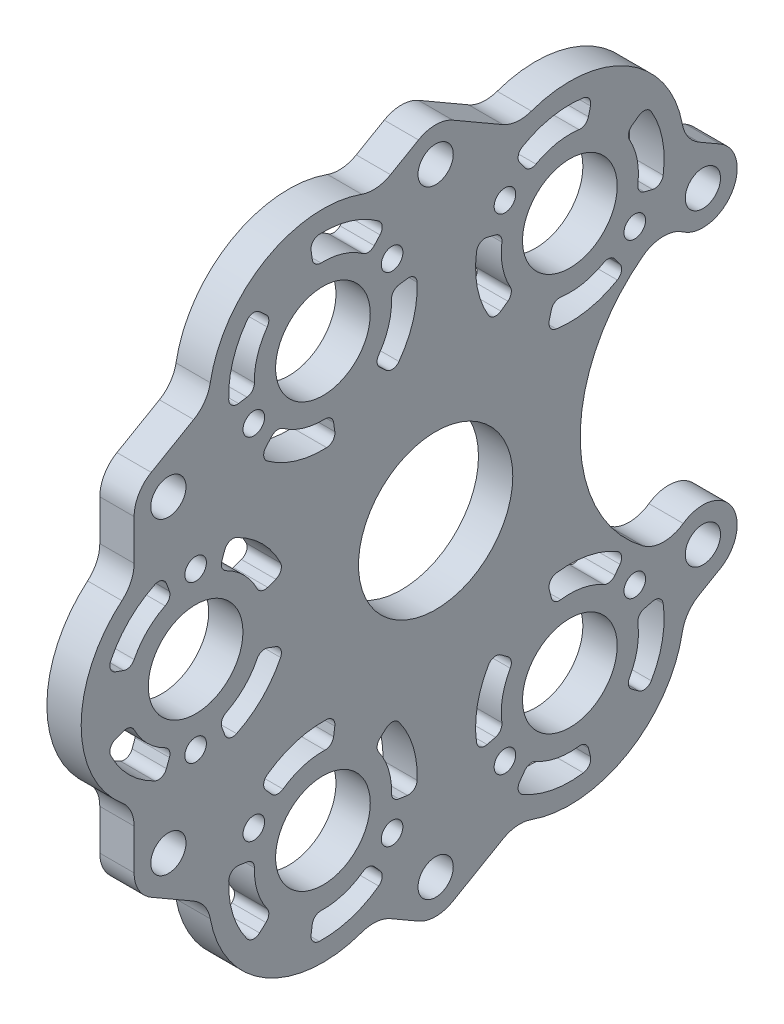
SolidWorks part; units mm, degrees
material "6061-T6 (SS)"
ref_plane "Front Plane" through (0, 0, 0) normal (0, 0, 1) x (1, 0, 0)
ref_plane "Top Plane" through (0, 0, 0) normal (0, 1, 0) x (1, 0, 0)
ref_plane "Right Plane" through (0, 0, 0) normal (1, 0, 0) x (0, 0, -1)
sketch "Sketch1" plane through (0, 0, 0) normal (1, 0, 0) x (0, 0, -1)
  line L0 (-49.4934, 28.575) -> (-49.4934, -28.575) construction
  line L1 (-49.4934, -28.575) -> (0, -57.15) construction
  line L2 (0, -57.15) -> (49.4934, -28.575) construction
  line L3 (49.4934, -28.575) -> (49.4934, 28.575) construction
  line L4 (49.4934, 28.575) -> (0, 57.15) construction
  line L5 (0, 57.15) -> (-49.4934, 28.575) construction
  line L6 (-55.8434, 32.2412) -> (-55.8434, -32.2412)
  line L7 (-55.8434, -32.2412) -> (0, -64.4823)
  line L8 (0, -64.4823) -> (55.8434, -32.2412)
  line L10 (55.8434, 32.2412) -> (0, 64.4823)
  line L11 (0, 64.4823) -> (-55.8434, 32.2412)
  line L12 (55.8434, -32.2412) -> (55.8434, 32.2412) construction
  line L13 (55.8434, -32.2412) -> (55.8434, -29.0662)
  line L14 (55.8434, -29.0662) -> (55.8434, 29.0662)
  line L15 (55.8434, 29.0662) -> (55.8434, 32.2412)
  circle A0 centre (49.4934, -28.575) radius 3.2639 construction
  circle A1 centre (0, 57.15) radius 3.2639 construction
  circle A2 centre (49.4934, 28.575) radius 3.2639 construction
  circle A3 centre (0, -57.15) radius 3.2639 construction
  circle A4 centre (-49.4934, -28.575) radius 3.2639 construction
  circle A5 centre (-49.4934, 28.575) radius 3.2639 construction
  circle A6 centre (49.4934, -28.575) radius 3.2639
  circle A7 centre (0, 57.15) radius 3.2639
  circle A8 centre (49.4934, 28.575) radius 3.2639
  circle A9 centre (0, -57.15) radius 3.2639
  circle A10 centre (-49.4934, -28.575) radius 3.2639
  circle A11 centre (-49.4934, 28.575) radius 3.2639
  circle A12 centre (-44.45, 14.4996) radius 2 construction
  circle A13 centre (-44.45, -14.4996) radius 2 construction
  circle A14 centre (-33.6704, -32.4399) radius 2 construction
  circle A15 centre (-8.0656, -46.0542) radius 2 construction
  circle A16 centre (12.8354, -44.9588) radius 2 construction
  circle A17 centre (36.8768, -28.7427) radius 2 construction
  circle A18 centre (36.8768, 28.7427) radius 2 construction
  circle A19 centre (12.8354, 44.9588) radius 2 construction
  circle A20 centre (-8.0656, 46.0542) radius 2 construction
  circle A21 centre (-33.6704, 32.4399) radius 2 construction
  circle A22 centre (-44.45, 0) radius 8.763 construction
  circle A23 centre (-20.868, -39.247) radius 8.763 construction
  circle A24 centre (24.8561, -36.8507) radius 8.763 construction
  circle A25 centre (24.8561, 36.8507) radius 8.763 construction
  circle A26 centre (-20.868, 39.247) radius 8.763 construction
  circle A27 centre (-44.45, 14.4996) radius 2
  circle A28 centre (-44.45, -14.4996) radius 2
  circle A29 centre (-33.6704, -32.4399) radius 2
  circle A30 centre (-8.0656, -46.0542) radius 2
  circle A31 centre (12.8354, -44.9588) radius 2
  circle A32 centre (36.8768, -28.7427) radius 2
  circle A33 centre (36.8768, 28.7427) radius 2
  circle A34 centre (12.8354, 44.9588) radius 2
  circle A35 centre (-8.0656, 46.0542) radius 2
  circle A36 centre (-33.6704, 32.4399) radius 2
  circle A37 centre (-44.45, 0) radius 8.763
  circle A38 centre (-20.868, -39.247) radius 8.763
  circle A39 centre (24.8561, -36.8507) radius 8.763
  circle A40 centre (24.8561, 36.8507) radius 8.763
  circle A41 centre (-20.868, 39.247) radius 8.763
  circle A42 centre (-20.868, -39.247) radius 21.1963 construction
  circle A43 centre (24.8561, -36.8507) radius 21.1963 construction
  circle A44 centre (24.8561, 36.8507) radius 21.1963 construction
  circle A45 centre (-20.868, 39.247) radius 21.1963 construction
  circle A46 centre (-44.45, 0) radius 21.1963 construction
  circle A47 centre (-20.868, -39.247) radius 21.1963
  circle A48 centre (24.8561, -36.8507) radius 21.1963
  circle A49 centre (24.8561, 36.8507) radius 21.1963
  circle A50 centre (-20.868, 39.247) radius 21.1963
  circle A51 centre (-44.45, 0) radius 21.1963
  arc A53 (55.8434, -29.0662) -> (55.8434, 29.0662) centre (55.8434, 0) cw
  circle A56 centre (49.4934, -28.575) radius 6.35
  circle A57 centre (49.4934, 28.575) radius 6.35
  circle A58 centre (0, 0) radius 14.2875 construction
  circle A59 centre (0, 0) radius 14.2875
  dimension "D3" = 12.7
  dimension "D2" = 3.175
  dimension "D1" = 6.35
extrude "Boss-Extrude1" add sketch "Sketch1" against normal blind 6.35 contours L13 A53 L15 L10 A49 L11 A50 L6 A51 L7 A47 L8 A48 A11 A10 A9 A8 A7 A6 | L6 A51 A27 A28 A37 | L11 A50 A35 A36 A41 | L10 A49 A33 A34 A40 | L10 A49 | L11 A50 | L8 A48 A31 A32 A39 | L7 A47 A29 A30 A38 | L7 A47 | L6 A51 | L8 A48 | A53 A56 A6 | A56 A53 A6 | A57 A53 A8 | A53 A57 A8 | A49 A57 | A57 L10 A49 | A56 A48 L8 | A48 A56 | A56 A53 A48 | A57 A49 A53
fillet "Fillet1" radius 6.35 16 edges at (-3.175, -55.7136, -15.1879) (-3.175, -37.9092, -46.026) (-3.175, -64.4823, 0) (-3.175, -40.2091, 42.0425) (-3.175, -58.0657, 11.114) (-3.175, -32.2412, 55.8434) (-3.175, 17.8739, 55.8434) (-3.175, -17.8739, 55.8434) (-3.175, 32.2412, 55.8434) (-3.175, 37.9092, -46.026) (-3.175, 55.7136, -15.1879) (-3.175, 64.4823, 0) (-3.175, 58.0657, 11.114) (-3.175, 40.2091, 42.0425) (-3.175, -26.3386, -43.5502) (-3.175, 26.3386, -43.5502)
sketch "Sketch2" plane through (-6.35, 0, 0) normal (-1, 0, 0) x (0, 0, 1)
  line L3 (28.0406, 5.9725) -> (44.45, 0)
  line L4 (44.45, 0) -> (38.4775, 16.4094)
  line L5 (44.45, 0) -> (26.9875, 0) construction
  line L6 (44.45, 17.4625) -> (44.45, 0) construction
  line L7 (41.4637, 8.2047) -> (36.2453, 2.9863) construction
  line L8 (36.2453, 2.9863) -> (36.2453, 0) construction
  line L9 (41.4637, 8.2047) -> (44.45, 8.2047) construction
  line L10 (50.4225, 16.4094) -> (44.45, 0)
  line L11 (44.45, 0) -> (60.8594, 5.9725)
  line L12 (60.8594, -5.9725) -> (44.45, 0)
  line L13 (44.45, 0) -> (50.4225, -16.4094)
  line L14 (38.4775, -16.4094) -> (44.45, 0)
  line L15 (44.45, 0) -> (28.0406, -5.9725)
  circle A0 centre (44.45, 0) radius 17.4625
  circle A1 centre (44.45, 0) radius 12.7
  point P21 (44.45, 0)
  dimension "D2" = 25.4
  dimension "D3" = 34.925
  dimension "D1" = 50
  dimension "D4" = 4
extrude "Cut-Extrude1" cut sketch "Sketch2" against normal through all contours A1 L4 A0 L3 | A1 L15 A0 L14 | A1 L13 A0 L12 | A1 L11 A0 L10
fillet "Fillet2" radius 1.5875 16 edges at (-3.175, 11.9341, 40.1063) (-3.175, 16.4094, 38.4775) (-3.175, 4.3437, 32.5159) (-3.175, 5.9725, 28.0406) (-3.175, -4.3437, 32.5159) (-3.175, -5.9725, 28.0406) (-3.175, -16.4094, 38.4775) (-3.175, -11.9341, 40.1063) (-3.175, -5.9725, 60.8594) (-3.175, -16.4094, 50.4225) (-3.175, -11.9341, 48.7937) (-3.175, -4.3437, 56.3841) (-3.175, 5.9725, 60.8594) (-3.175, 4.3437, 56.3841) (-3.175, 11.9341, 48.7937) (-3.175, 16.4094, 50.4225)
pattern_circular "CirPattern4" count 3 every 62 about axis through (0, 0, 0) along (1, 0, 0) of "Cut-Extrude1", "Fillet2"
pattern_circular "CirPattern5" count 3 every 62 about axis through (0, 0, 0) along (1, 0, 0) of "Cut-Extrude1", "Fillet2"
